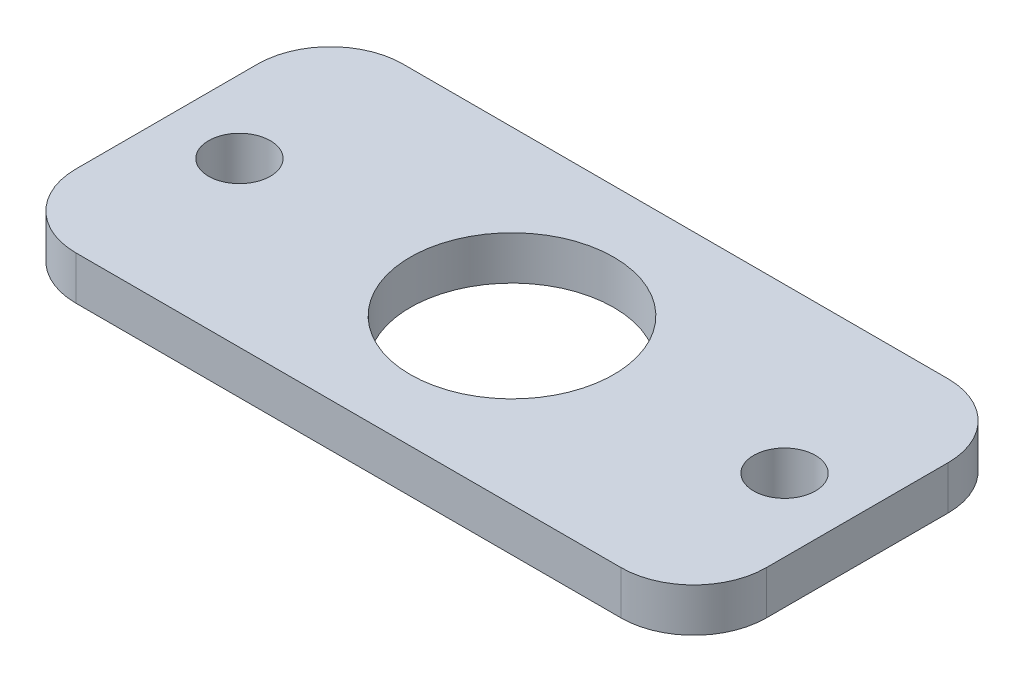
SolidWorks part; units mm, degrees
ref_plane "Front Plane" through (0, 0, 0) normal (0, 0, 1) x (1, 0, 0)
ref_plane "Top Plane" through (0, 0, 0) normal (0, 1, 0) x (1, 0, 0)
ref_plane "Right Plane" through (0, 0, 0) normal (1, 0, 0) x (0, 0, -1)
sketch "Sketch1" plane through (0, 0, 0) normal (0, 1, 0) x (1, 0, 0)
  line L0 (0, -55) -> (0, 55) construction
  line L1 (-47.5, -22.5) -> (47.5, -22.5)
  line L2 (-47.5, -22.5) -> (-47.5, 22.5)
  line L3 (-47.5, 22.5) -> (47.5, 22.5)
  line L4 (47.5, -22.5) -> (47.5, 22.5)
  line L5 (-47.5, -22.5) -> (47.5, 22.5) construction
  line L6 (-47.5, 22.5) -> (47.5, -22.5) construction
  circle A0 centre (0, 0) radius 14
  circle A1 centre (37.5, 0) radius 4.25
  circle A2 centre (-37.5, 0) radius 4.25
  point P0 (0, 0)
  point P14 (0, 0)
  dimension "D3" = 28
  dimension "D4" = 8.5
  dimension "D1" = 45
  dimension "D2" = 95
  dimension "D5" = 75
extrude "Boss-Extrude1" add sketch "Sketch1" along normal blind 6
fillet "Fillet1" radius 10 4 edges at (-47.5, 3, -22.5) (47.5, 3, -22.5) (47.5, 3, 22.5) (-47.5, 3, 22.5)
